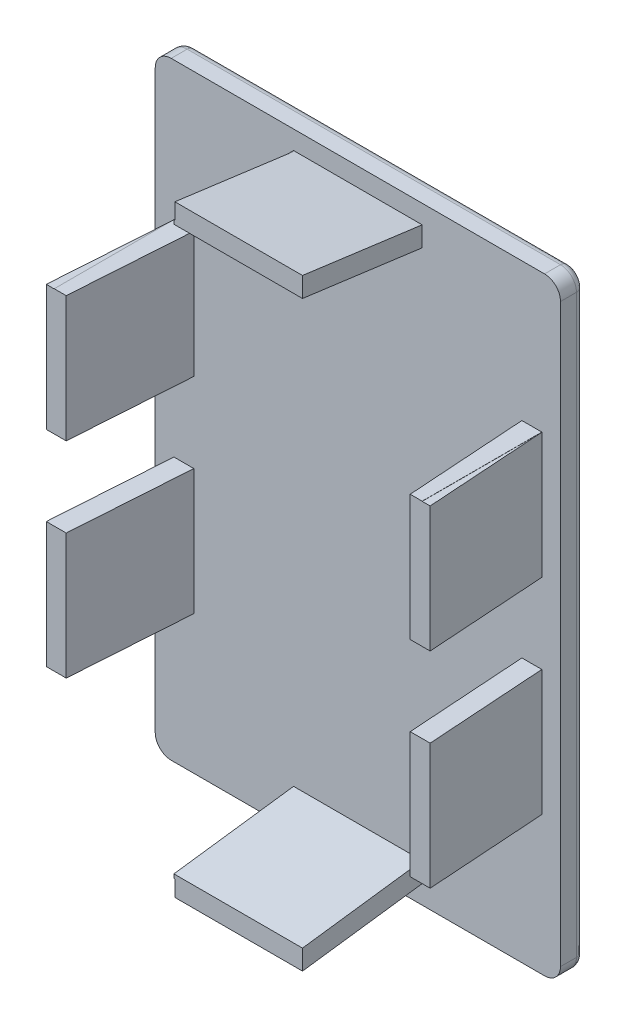
SolidWorks part; units mm, degrees
material "PLA"
ref_plane "Alzado" through (0, 0, 0) normal (0, 0, 1) x (1, 0, 0)
ref_plane "Planta" through (0, 0, 0) normal (0, 1, 0) x (1, 0, 0)
ref_plane "Vista lateral" through (0, 0, 0) normal (1, 0, 0) x (0, 0, -1)
sketch "Croquis1" plane through (0, 0, 0) normal (0, 0, 1) x (1, 0, 0)
  line L1 (25.4, 38.1) -> (-25.4, 38.1)
  line L2 (25.4, 38.1) -> (25.4, -38.1)
  line L3 (25.4, -38.1) -> (-25.4, -38.1)
  line L4 (-25.4, 38.1) -> (-25.4, -38.1)
  line L5 (25.4, 38.1) -> (-25.4, -38.1) construction
  line L6 (25.4, -38.1) -> (-25.4, 38.1) construction
  point P0 (0, 0)
  dimension "D1" = 76.2
  dimension "D2" = 50.8
extrude "Saliente-Extruir1" add sketch "Croquis1" along normal blind 18
sketch "Croquis2" plane through (0, 0, 18) normal (0, 0, 1) x (1, 0, 0)
  line L0 (25.4, 38.1) -> (-25.4, 38.1) construction
  line L1 (-23.06, 35.76) -> (23.06, 35.76)
  line L2 (-23.06, 35.76) -> (-23.06, -35.76)
  line L3 (-23.06, -35.76) -> (23.06, -35.76)
  line L4 (23.06, 35.76) -> (23.06, -35.76)
  line L5 (-25.4, -38.1) -> (25.4, -38.1) construction
  line L6 (-25.4, 38.1) -> (-25.4, -38.1) construction
  line L7 (25.4, -38.1) -> (25.4, 38.1) construction
  line L9 (-25.4, 38.1) -> (25.4, 38.1)
  line L10 (-25.4, 38.1) -> (-25.4, -38.1)
  line L11 (-25.4, -38.1) -> (25.4, -38.1)
  line L12 (25.4, 38.1) -> (25.4, -38.1)
  line L13 (-19.4, 32.1) -> (19.4, 32.1)
  line L14 (-19.4, 32.1) -> (-19.4, -32.1)
  line L15 (-19.4, -32.1) -> (19.4, -32.1)
  line L16 (19.4, 32.1) -> (19.4, -32.1)
  line M9 (-25.4, 38.1) -> (-25.4, -38.1)
  line M10 (-25.4, -38.1) -> (25.4, -38.1)
  line M11 (25.4, -38.1) -> (25.4, 38.1)
  line M12 (25.4, 38.1) -> (-25.4, 38.1)
  dimension "D1" = 2.34
  dimension "D2" = 2.34
  dimension "D3" = 2.34
  dimension "D4" = 2.34
  dimension "D5" = 6
  dimension "D6" = 6
  dimension "D7" = 6
  dimension "D8" = 6
extrude "Cortar-Extruir1" cut sketch "Croquis2" against normal blind 15 contours L1 L4 L3 L2 M12 M9 M10 M11 | L16 L13 L14 L15
sketch "Croquis3" plane through (0, 0, 18) normal (0, 0, 1) x (1, 0, 0)
  line L0 (-23.06, 35.76) -> (-23.06, -35.76) construction
  line L1 (-23.06, 22.1) -> (-19.4, 22.1)
  line L2 (-23.06, 22.1) -> (-23.06, -22.1)
  line L3 (-23.06, -22.1) -> (-19.4, -22.1)
  line L4 (-19.4, 22.1) -> (-19.4, -22.1)
  line L5 (-19.4, 32.1) -> (-19.4, -32.1) construction
  line L6 (-19.4, -32.1) -> (19.4, -32.1) construction
  line L7 (-9.4, -32.1) -> (9.3837, -32.1)
  line L8 (-9.4, -32.1) -> (-9.4, -35.76)
  line L9 (-9.4, -35.76) -> (9.3837, -35.76)
  line L10 (9.3837, -32.1) -> (9.3837, -35.76)
  line L11 (-23.06, -35.76) -> (23.06, -35.76) construction
  line L12 (19.4, 32.1) -> (19.4, -32.1) construction
  line L13 (19.4, -22.1) -> (23.06, -22.1)
  line L14 (19.4, -22.1) -> (19.4, 22.1)
  line L15 (19.4, 22.1) -> (23.06, 22.1)
  line L16 (23.06, -22.1) -> (23.06, 22.1)
  line L17 (23.06, 35.76) -> (23.06, -35.76) construction
  line L18 (-23.06, 35.76) -> (23.06, 35.76) construction
  line L19 (-9.4, 35.76) -> (9.4, 35.76)
  line L20 (-9.4, 35.76) -> (-9.4, 32.1)
  line L21 (-9.4, 32.1) -> (9.4, 32.1)
  line L22 (9.4, 35.76) -> (9.4, 32.1)
  line L23 (-19.4, 32.1) -> (19.4, 32.1) construction
  line L24 (-19.4, 32.1) -> (-19.4, -32.1) construction
  line L25 (19.4, 32.1) -> (19.4, -32.1) construction
  dimension "D1" = 10
  dimension "D2" = 10
  dimension "D3" = 10
  dimension "D4" = 10
  dimension "D5" = 10
  dimension "D6" = 10
  dimension "D7" = 10
extrude "Cortar-Extruir2" [suppressed] cut sketch "Croquis3" against normal blind 7
fillet "Redondeo1" [suppressed] radius 2
fillet "Redondeo2" [suppressed] radius 1
sketch "Croquis5" [suppressed] plane through (0, -38.1, 0) normal (0, -1, 0) x (1, 0, 0)
  line L0 (-23.4, 3) -> (23.4, 3) construction
  line L1 (-3, 3) -> (3, 3)
  line L2 (-3, 3) -> (-3, 1.5)
  line L3 (-3, 1.5) -> (3, 1.5)
  line L4 (3, 3) -> (3, 1.5)
  line L5 (0, 1) -> (0, 3) construction
  line L6 (-23.4, 1) -> (23.4, 1) construction
  dimension "D1" = 3
  dimension "D2" = 3
  dimension "D3" = 1.5
extrude "Cortar-Extruir4" [suppressed] cut sketch "Croquis5" against normal blind 6
sketch "Croquis6" plane through (0, 0, 18) normal (0, 0, 1) x (1, 0, 0)
  line L0 (-23.06, 35.76) -> (-8.06, 35.76)
  line L1 (-23.06, 35.76) -> (23.06, 35.76) construction
  line L2 (-8.06, 35.76) -> (-8.06, 32.1)
  line L3 (-19.4, 32.1) -> (19.4, 32.1) construction
  line L4 (-8.06, 32.1) -> (-19.4, 32.1)
  line L5 (-19.4, 32.1) -> (-19.4, 20.76)
  line L6 (-19.4, 32.1) -> (-19.4, -32.1) construction
  line L7 (-19.4, 20.76) -> (-23.06, 20.76)
  line L8 (-23.06, 35.76) -> (-23.06, -35.76) construction
  line L9 (-23.06, 20.76) -> (-23.06, 35.76)
  line L10 (23.06, 35.76) -> (8.06, 35.76)
  line L11 (-23.06, 35.76) -> (23.06, 35.76) construction
  line L12 (8.06, 35.76) -> (8.06, 32.1)
  line L13 (8.06, 32.1) -> (19.4, 32.1)
  line L14 (19.4, 32.1) -> (19.4, -32.1) construction
  line L15 (19.4, 32.1) -> (19.4, -32.1) construction
  line L16 (19.4, 32.1) -> (19.4, 20.76)
  line L17 (19.4, 20.76) -> (23.06, 20.76)
  line L18 (23.06, 35.76) -> (23.06, -35.76) construction
  line L19 (23.06, 20.76) -> (23.06, 35.76)
  line L20 (-23.06, -35.76) -> (-23.06, -20.76)
  line L21 (-23.06, 35.76) -> (-23.06, -35.76) construction
  line L22 (-23.06, -20.76) -> (-19.4, -20.76)
  line L23 (-19.4, 32.1) -> (-19.4, -32.1) construction
  line L24 (-19.4, -20.76) -> (-19.4, -32.1)
  line L25 (-19.4, -32.1) -> (-8.06, -32.1)
  line L26 (-19.4, -32.1) -> (19.4, -32.1) construction
  line L27 (-8.06, -32.1) -> (-8.06, -35.76)
  line L28 (-23.06, -35.76) -> (23.06, -35.76) construction
  line L29 (-8.06, -35.76) -> (-23.06, -35.76)
  line L30 (23.06, -35.76) -> (8.06, -35.76)
  line L31 (-23.06, -35.76) -> (23.06, -35.76) construction
  line L32 (8.06, -35.76) -> (8.06, -32.1)
  line L33 (-19.4, -32.1) -> (19.4, -32.1) construction
  line L34 (8.06, -32.1) -> (19.4, -32.1)
  line L35 (19.4, -32.1) -> (19.4, -20.76)
  line L36 (19.4, -20.76) -> (23.06, -20.76)
  line L37 (23.06, 35.76) -> (23.06, -35.76) construction
  line L38 (23.06, -20.76) -> (23.06, -35.76)
  dimension "D1" = 15
  dimension "D2" = 15
  dimension "D3" = 15
  dimension "D4" = 15
  dimension "D5" = 15
  dimension "D6" = 15
  dimension "D7" = 15
  dimension "D8" = 15
extrude "Cortar-Extruir8" cut sketch "Croquis6" against normal blind 15
sketch "Croquis10" plane through (0, -20.76, 0) normal (0, -1, 0) x (-1, 0, 0)
  line L0 (23.06, -18) -> (24.06, -18)
  line L1 (24.06, -18) -> (23.06, -3)
  line L2 (23.06, -3) -> (23.06, -18)
  line L3 (-23.06, -18) -> (-24.06, -18)
  line L4 (-24.06, -18) -> (-23.06, -3)
  line L5 (-23.06, -3) -> (-23.06, -18)
  dimension "D1" = 1
  dimension "D2" = 1
extrude "Saliente-Extruir3" add sketch "Croquis10" against normal blind 41.5
sketch "Croquis11" plane through (0, -20.76, 0) normal (0, -1, 0) x (1, 0, 0)
  line L0 (-19.4, 18) -> (-21.56, 18)
  line L1 (-19.4, 18) -> (-24.06, 18) construction
  line L2 (-21.56, 18) -> (-20.56, 3)
  line L3 (-19.4, 3) -> (-23.06, 3) construction
  line L4 (-20.56, 3) -> (-19.4, 3)
  line L5 (-19.4, 18) -> (-19.4, 3)
  dimension "D1" = 2.5
  dimension "D2" = 1.16
extrude "Cortar-Extruir9" cut sketch "Croquis11" against normal blind 51.5
sketch "Croquis12" plane through (0, -20.76, 0) normal (0, -1, 0) x (1, 0, 0)
  line L0 (19.4, 18) -> (19.4, 3)
  line L1 (19.4, 3) -> (20.56, 3)
  line L2 (23.06, 3) -> (19.4, 3) construction
  line L3 (20.56, 3) -> (21.56, 18)
  line L4 (24.06, 18) -> (19.4, 18) construction
  line L5 (21.56, 18) -> (19.4, 18)
  dimension "D1" = 2.5
  dimension "D2" = 1.16
extrude "Cortar-Extruir10" cut sketch "Croquis12" against normal blind 51.5
sketch "Croquis13" plane through (8.06, 0, 0) normal (1, 0, 0) x (0, 0, -1)
  line L0 (-18, -35.76) -> (-18, -37.76)
  line L1 (-18, -37.76) -> (-3, -35.76)
  line L2 (-3, -35.76) -> (-18, -35.76)
  line L3 (-18, 35.76) -> (-18, 37.76)
  line L4 (-18, 37.76) -> (-3, 35.76)
  line L5 (-3, 35.76) -> (-18, 35.76)
  dimension "D1" = 2
  dimension "D2" = 2
extrude "Saliente-Extruir4" add sketch "Croquis13" against normal blind 16
sketch "Croquis14" plane through (8.06, 0, 0) normal (1, 0, 0) x (0, 0, -1)
  line L0 (-3, -32.1) -> (-18, -32.1)
  line L1 (-18, -32.1) -> (-18, -35.26)
  line L2 (-18, -32.1) -> (-18, -37.76) construction
  line L3 (-18, -35.26) -> (-3, -33.26)
  line L4 (-3, -32.1) -> (-3, -35.76) construction
  line L5 (-3, -33.26) -> (-3, -32.1)
  line L6 (-18, 32.1) -> (-18, 35.26)
  line L7 (-18, 37.76) -> (-18, 32.1) construction
  line L8 (-18, 35.26) -> (-3, 33.26)
  line L9 (-3, 35.76) -> (-3, 32.1) construction
  line L10 (-3, 33.26) -> (-3, 32.1)
  line L11 (-3, 32.1) -> (-18, 32.1)
  dimension "D1" = 2.5
  dimension "D2" = 1.16
  dimension "D3" = 2.5
  dimension "D4" = 1.16
extrude "Cortar-Extruir11" cut sketch "Croquis14" against normal blind 16.5
fillet "Redondeo3" radius 2 4 edges at (25.4, 38.1, 1.5) (-25.4, 38.1, 1.5) (-25.4, -38.1, 1.5) (25.4, -38.1, 1.5)
fillet "Redondeo4" radius 1 8 edges at (-24.8142, 37.5142, 0) (-25.4, 0, 0) (-24.8142, -37.5142, 0) (0, -38.1, 0) (24.8142, -37.5142, 0) (25.4, 0, 0) (24.8142, 37.5142, 0) (0, 38.1, 0)
sketch "Croquis15" plane through (0, 0, 18) normal (0, 0, 1) x (1, 0, 0)
  line L0 (-24.06, -0.01) -> (24.06, -0.01) construction
  line L1 (-24.06, 20.74) -> (-24.06, -20.76) construction
  line L2 (24.06, 20.74) -> (24.06, -20.76) construction
  line L4 (-24.06, 4.99) -> (24.06, 4.99)
  line L5 (-24.06, 4.99) -> (-24.06, -5.01)
  line L6 (-24.06, -5.01) -> (24.06, -5.01)
  line L7 (24.06, 4.99) -> (24.06, -5.01)
  dimension "D1" = 5
  dimension "D2" = 5
extrude "Cortar-Extruir12" cut sketch "Croquis15" against normal blind 15
sketch "Croquis16" plane through (0, -38.1, 0) normal (0, -1, 0) x (1, 0, 0)
  line L0 (-23.4, 3) -> (23.4, 3) construction
  line L1 (-4, 3) -> (4, 3)
  line L2 (-4, 3) -> (-4, 1.5)
  line L3 (-4, 1.5) -> (4, 1.5)
  line L4 (4, 3) -> (4, 1.5)
  dimension "D1" = 1.5
  dimension "D2" = 8
  dimension "D3" = 4
extrude "Cortar-Extruir13" cut sketch "Croquis16" against normal blind 2
sketch "Croquis17" plane through (0, 0, 3) normal (0, 0, 1) x (1, 0, 0)
  line L0 (-25.4, 36.1) -> (-25.4, -36.1) construction
  line L1 (-23.4, -38.1) -> (-4, -38.1) construction
  circle A0 centre (-13.4, -23.1) radius 3
  dimension "D2" = 6
  dimension "D1" = 12
  dimension "D3" = 15
extrude "Cortar-Extruir14" [suppressed] cut sketch "Croquis17" against normal blind 10
